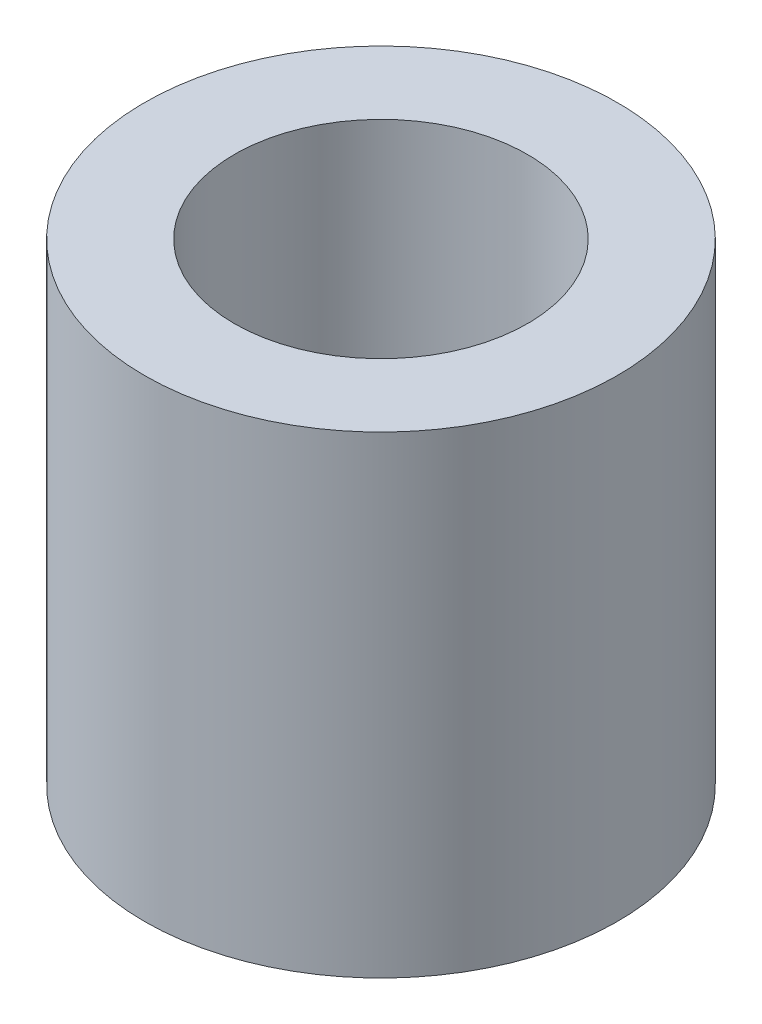
SolidWorks part; units mm, degrees
ref_plane "Front Plane" through (0, 0, 0) normal (0, 0, 1) x (1, 0, 0)
ref_plane "Top Plane" through (0, 0, 0) normal (0, 1, 0) x (1, 0, 0)
ref_plane "Right Plane" through (0, 0, 0) normal (1, 0, 0) x (0, 0, -1)
sketch "Sketch1" plane through (0, 0, 0) normal (0, 1, 0) x (1, 0, 0)
  circle A0 centre (0, 0) radius 3.1
  circle A1 centre (0, 0) radius 5
  dimension "D1" = 6.2
  dimension "D2" = 10
extrude "Boss-Extrude1" add sketch "Sketch1" along normal blind 10
